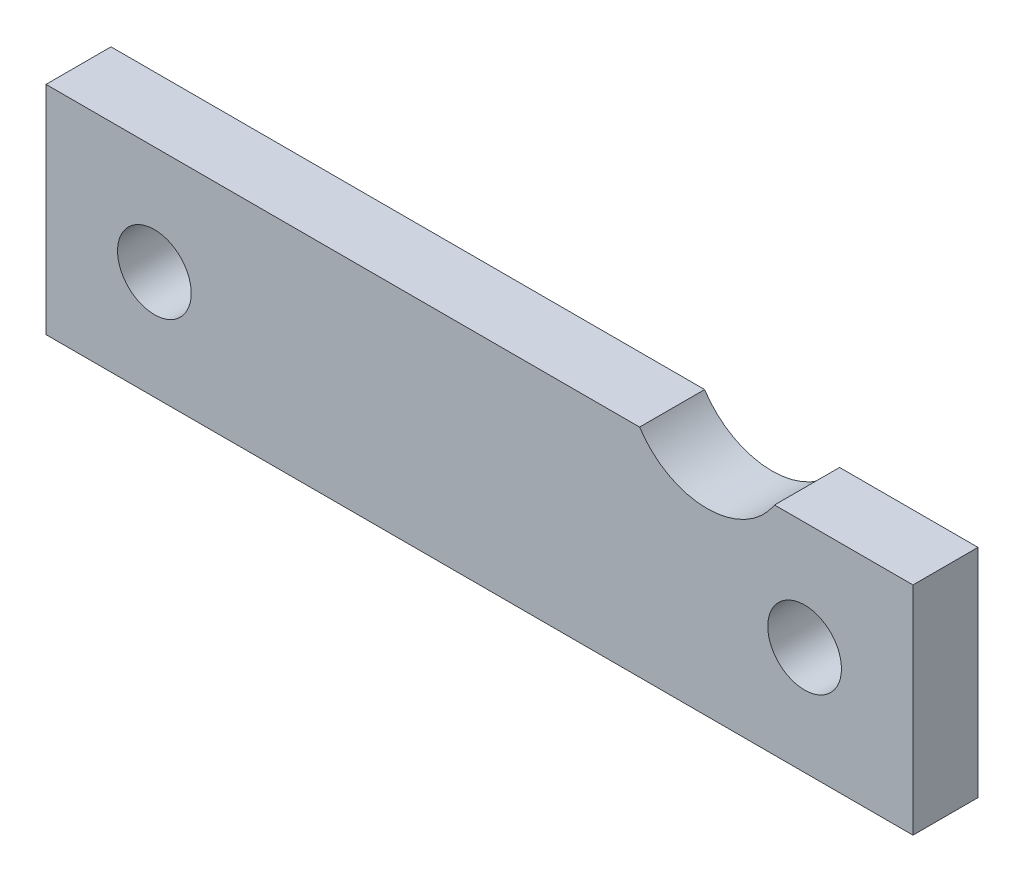
SolidWorks part; units mm, degrees
other "Platform Joint Strap 2 Left"
ref_plane "Front Plane" through (0, 0, 0) normal (0, 0, 1) x (1, 0, 0)
ref_plane "Top Plane" through (0, 0, 0) normal (0, 1, 0) x (1, 0, 0)
ref_plane "Right Plane" through (0, 0, 0) normal (1, 0, 0) x (0, 0, -1)
sketch3d "Main Profile Sketch datum points"
  point P0 (0, 0, 44.5)
  point P1 (10, 0, 44.5)
  point P2 (0, 10, 44.5)
ref_plane "Main Profile Sketch plane" through (0, 0, 44.5) normal (0, 0, 1) x (1, 0, 0)
sketch "Main Profile Sketch" plane through (0, 0, 44.5) normal (0, 0, 1) x (1, 0, 0)
  line L0 (35, 41.5) -> (62.3871, 41.5)
  line L1 (68.6129, 41.5) -> (75, 41.5)
  line L2 (75, 41.5) -> (75, 31.5)
  line L3 (35, 31.5) -> (75, 31.5)
  line L4 (35, 41.5) -> (35, 31.5)
  arc A0 (62.3871, 41.5) -> (68.6129, 41.5) centre (65.5, 43.5) ccw
  circle A1 centre (40, 36.5) radius 1.7
  circle A2 centre (70, 36.5) radius 1.7
extrude "Main Extrusion" add sketch "Main Profile Sketch" against normal blind 3 separate body
